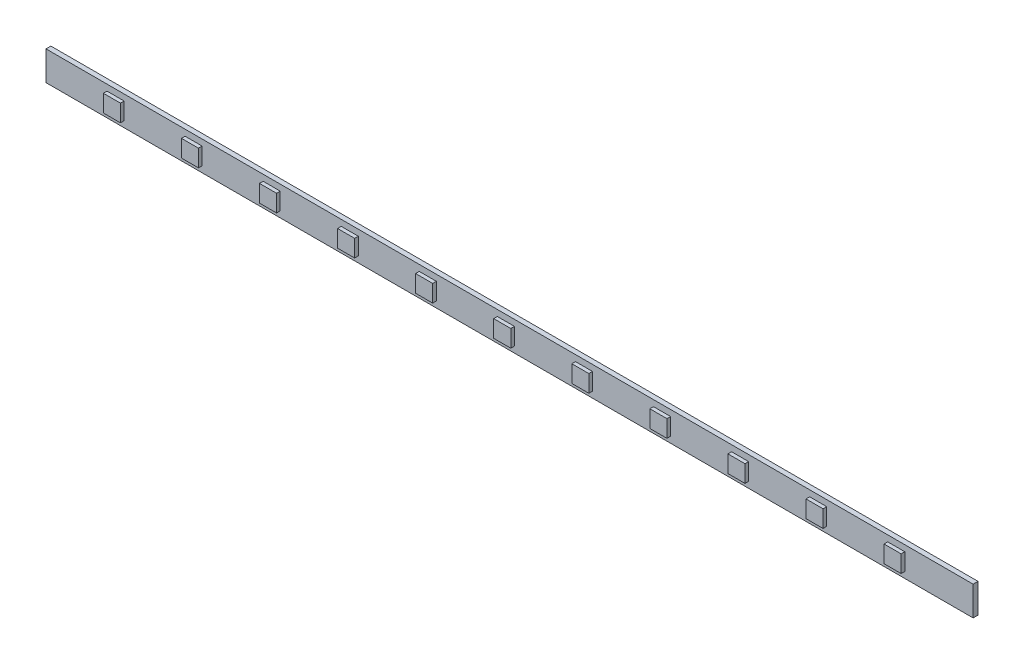
SolidWorks part; units mm, degrees
ref_plane "Front Plane" through (0, 0, 0) normal (0, 0, 1) x (1, 0, 0)
ref_plane "Top Plane" through (0, 0, 0) normal (0, 1, 0) x (1, 0, 0)
ref_plane "Right Plane" through (0, 0, 0) normal (1, 0, 0) x (0, 0, -1)
sketch "Sketch1" plane through (0, 0, 0) normal (0, 0, 1) x (1, 0, 0)
  line L1 (0, 0) -> (380, 0)
  line L2 (0, 0) -> (0, 12)
  line L3 (0, 12) -> (380, 12)
  line L4 (380, 0) -> (380, 12)
  dimension "D1" = 380
  dimension "D2" = 12
extrude "Boss-Extrude1" add sketch "Sketch1" along normal blind 2
sketch "Sketch2" plane through (0, 0, 2) normal (0, 0, 1) x (1, 0, 0)
  line L0 (0, 0) -> (25, 0) construction
  line L1 (0, 0) -> (380, 0) construction
  line L2 (25, 0) -> (25, 2.5) construction
  line L3 (32, 2.5) -> (32, 0) construction
  line L4 (25, 2.5) -> (32, 2.5)
  line L5 (25, 2.5) -> (25, 9.5)
  line L6 (25, 9.5) -> (32, 9.5)
  line L7 (32, 2.5) -> (32, 9.5)
  line L8 (64, 2.5) -> (64, 0) construction
  line L9 (57, 2.5) -> (57, 9.5)
  line L10 (57, 0) -> (57, 2.5) construction
  line L11 (64, 2.5) -> (64, 9.5)
  line L12 (32, 0) -> (57, 0) construction
  line L13 (57, 2.5) -> (64, 2.5)
  line L14 (57, 9.5) -> (64, 9.5)
  line L15 (96, 2.5) -> (96, 0) construction
  line L16 (89, 2.5) -> (89, 9.5)
  line L17 (89, 0) -> (89, 2.5) construction
  line L18 (96, 2.5) -> (96, 9.5)
  line L19 (64, 0) -> (89, 0) construction
  line L20 (89, 2.5) -> (96, 2.5)
  line L21 (89, 9.5) -> (96, 9.5)
  line L22 (128, 2.5) -> (128, 0) construction
  line L23 (121, 2.5) -> (121, 9.5)
  line L24 (121, 0) -> (121, 2.5) construction
  line L25 (128, 2.5) -> (128, 9.5)
  line L26 (96, 0) -> (121, 0) construction
  line L27 (121, 2.5) -> (128, 2.5)
  line L28 (121, 9.5) -> (128, 9.5)
  line L29 (160, 2.5) -> (160, 0) construction
  line L30 (153, 2.5) -> (153, 9.5)
  line L31 (153, 0) -> (153, 2.5) construction
  line L32 (160, 2.5) -> (160, 9.5)
  line L33 (128, 0) -> (153, 0) construction
  line L34 (153, 2.5) -> (160, 2.5)
  line L35 (153, 9.5) -> (160, 9.5)
  line L36 (192, 2.5) -> (192, 0) construction
  line L37 (185, 2.5) -> (185, 9.5)
  line L38 (185, 0) -> (185, 2.5) construction
  line L39 (192, 2.5) -> (192, 9.5)
  line L40 (160, 0) -> (185, 0) construction
  line L41 (185, 2.5) -> (192, 2.5)
  line L42 (185, 9.5) -> (192, 9.5)
  line L43 (224, 2.5) -> (224, 0) construction
  line L44 (217, 2.5) -> (217, 9.5)
  line L45 (217, 0) -> (217, 2.5) construction
  line L46 (224, 2.5) -> (224, 9.5)
  line L47 (192, 0) -> (217, 0) construction
  line L48 (217, 2.5) -> (224, 2.5)
  line L49 (217, 9.5) -> (224, 9.5)
  line L50 (256, 2.5) -> (256, 0) construction
  line L51 (249, 2.5) -> (249, 9.5)
  line L52 (249, 0) -> (249, 2.5) construction
  line L53 (256, 2.5) -> (256, 9.5)
  line L54 (224, 0) -> (249, 0) construction
  line L55 (249, 2.5) -> (256, 2.5)
  line L56 (249, 9.5) -> (256, 9.5)
  line L57 (288, 2.5) -> (288, 0) construction
  line L58 (281, 2.5) -> (281, 9.5)
  line L59 (281, 0) -> (281, 2.5) construction
  line L60 (288, 2.5) -> (288, 9.5)
  line L61 (256, 0) -> (281, 0) construction
  line L62 (281, 2.5) -> (288, 2.5)
  line L63 (281, 9.5) -> (288, 9.5)
  line L64 (320, 2.5) -> (320, 0) construction
  line L65 (313, 2.5) -> (313, 9.5)
  line L66 (313, 0) -> (313, 2.5) construction
  line L67 (320, 2.5) -> (320, 9.5)
  line L68 (288, 0) -> (313, 0) construction
  line L69 (313, 2.5) -> (320, 2.5)
  line L70 (313, 9.5) -> (320, 9.5)
  line L71 (352, 2.5) -> (352, 0) construction
  line L72 (345, 2.5) -> (345, 9.5)
  line L73 (345, 0) -> (345, 2.5) construction
  line L74 (352, 2.5) -> (352, 9.5)
  line L75 (320, 0) -> (345, 0) construction
  line L76 (345, 2.5) -> (352, 2.5)
  line L77 (345, 9.5) -> (352, 9.5)
  dimension "D1" = 25
  dimension "D2" = 2.5
  dimension "D3" = 7
  dimension "D4" = 7
extrude "Boss-Extrude2" add sketch "Sketch2" along normal blind 1.5
